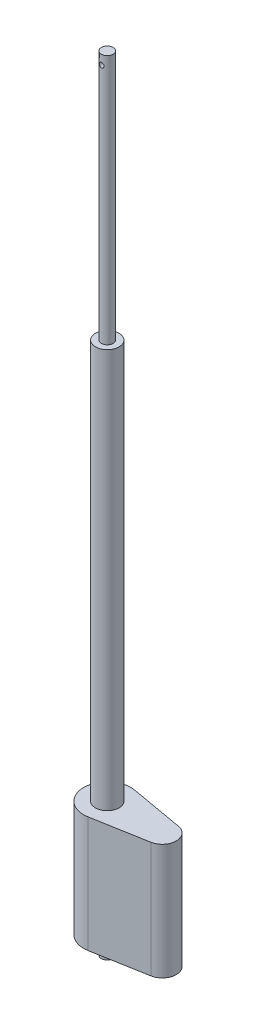
SolidWorks part; units mm, degrees
ref_plane "Front" through (0, 0, 0) normal (0, 0, 1) x (1, 0, 0)
ref_plane "Top" through (0, 0, 0) normal (0, 1, 0) x (1, 0, 0)
ref_plane "Right" through (0, 0, 0) normal (1, 0, 0) x (0, 0, -1)
sketch "Sketch7" plane through (0, 0, 0) normal (1, 0, 0) x (0, 0, -1)
  line L1 (-20, 7) -> (-20, 105)
  line L4 (-10, 443) -> (-5, 443)
  line L5 (-5, 443) -> (-5, 655)
  line L6 (-5, 655) -> (0, 655)
  line L7 (0, 655) -> (0, -8)
  line L9 (-5, -8) -> (0, -8)
  line L10 (-10, 443) -> (-10, 105)
  line L11 (-10, 105) -> (-20, 105)
  line L12 (-5, -8) -> (-5, 7)
  line L13 (-5, 7) -> (-20, 7)
  point P11 (0, 0)
  point P12 (0, 647)
  point P13 (0, 455)
  dimension "D1" = 8
  dimension "D2" = 8
  dimension "D3" = 98
  dimension "D5" = 12
  dimension "D7" = 10
  dimension "D8" = 20
  dimension "D11" = 5
  dimension "D9" = 15
  dimension "D10" = 5
  dimension "D4" = 200
  dimension "D6" = 455
revolve "Revolve2" add sketch "Sketch7" angle 360 about L7
sketch "Sketch8" plane through (0, 0, 0) normal (0, 0, 1) x (1, 0, 0)
  line L0 (-5, -8) -> (5, -8) construction
  line L2 (0, 655) -> (0, 647) construction
  line L3 (5, 655) -> (-5, 655) construction
  line L4 (-5, -8) -> (5, -8) construction
  line L5 (0, -8) -> (0, 0) construction
  circle A1 centre (0, 647) radius 2
  circle A2 centre (0, 0) radius 2
  dimension "D2" = 8
  dimension "D1" = 4
  dimension "D4" = 4
  dimension "D3" = 8
extrude "Cut-Extrude2" cut sketch "Sketch8" against normal through all and the other way through all
sketch "Sketch10" plane through (0, 105, 0) normal (0, 1, 0) x (1, 0, 0)
  line L0 (0, 0) -> (46.5567, 0) construction
  line L1 (3.491, 19.693) -> (48.6292, 11.6912)
  line L2 (48.6292, -11.6912) -> (3.491, -19.693)
  circle A1 centre (0, 0) radius 20 construction
  arc A2 (48.6292, 11.6912) -> (48.6292, -11.6912) centre (46.5567, 0) cw
  arc A3 (3.491, 19.693) -> (3.491, -19.693) centre (0, 0) ccw
extrude "Boss-Extrude4" add sketch "Sketch10" against normal up to surface (98 mm away) up to face at (0, 7, 5)
sketch "Sketch11" plane through (0, 0, 0) normal (0, 0, 1) x (1, 0, 0)
  line L0 (0, 647) -> (0, 0)
equation "\"mountingHoleDistance\"=8"
equation "\"actuatorLength\"= 200"
equation "\"D1@Sketch7\"= \"mountingHoleDistance\""
equation "\"D2@Sketch7\"=\"mountingHoleDistance\""
equation "\"MotorHousingHeight\"= 98"
equation "\"D3@Sketch7\"=\"MotorHousingHeight\""
equation "\"acutatorMinimumLength\"= 455"
equation "\"D3@Sketch8\"=\"mountingHoleDistance\""
equation "\"D2@Sketch8\"=\"mountingHoleDistance\""
equation "\"D4@Sketch7\"=\"actuatorLength\""
equation "\"D6@Sketch7\"=\"acutatorMinimumLength\""
